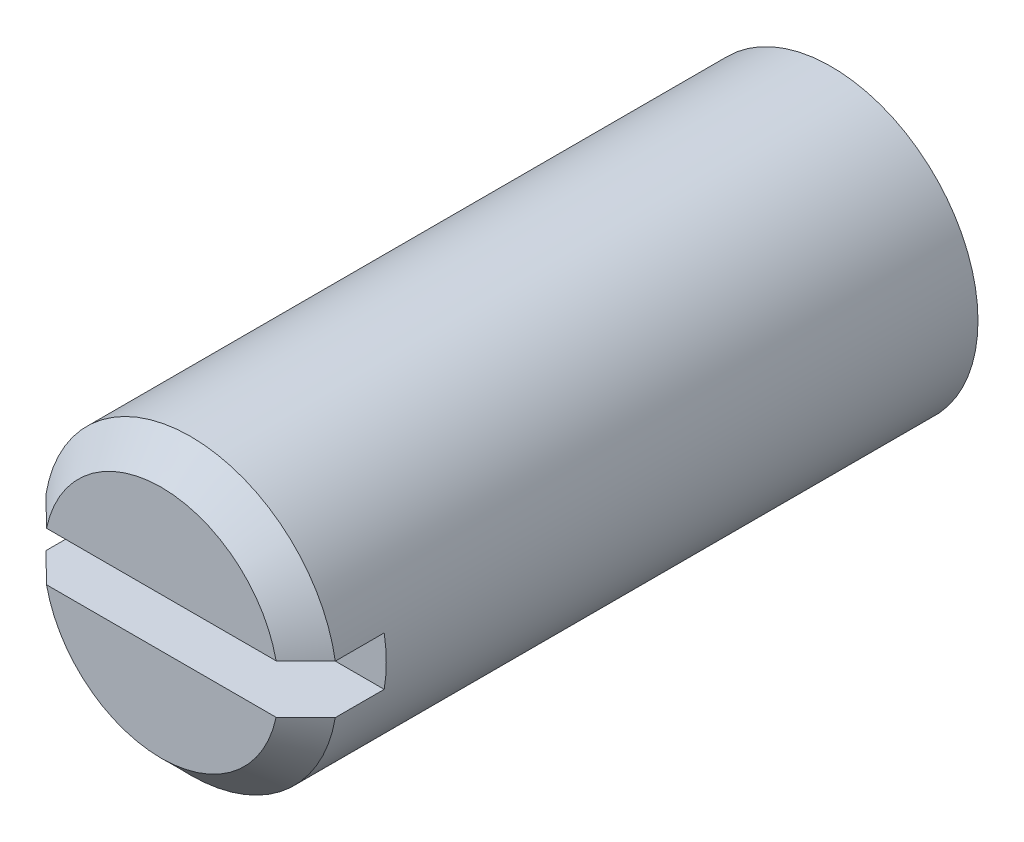
SolidWorks part; units mm, degrees
ref_plane "Спереди" through (0, 0, 0) normal (0, 0, 1) x (1, 0, 0)
ref_plane "Сверху" through (0, 0, 0) normal (0, 1, 0) x (1, 0, 0)
ref_plane "Справа" through (0, 0, 0) normal (1, 0, 0) x (0, 0, -1)
sketch "Эскиз1" plane through (0, 0, 0) normal (0, 1, 0) x (1, 0, 0)
  line L0 (0, 0) -> (-3, 0)
  line L1 (-3, 0) -> (-3, 13.701)
  line L2 (-0.75, 15) -> (0, 15)
  line L3 (0, 15) -> (0, 0)
  line L4 (-0.75, 15) -> (-3, 13.701)
  dimension "D1" = 0.75
  dimension "D2" = 3
  dimension "D3" = 15
  dimension "D4" = 60
revolve "Повернуть1" add sketch "Эскиз1" angle 360 about L3
sketch "Эскиз2" plane through (0, 0, 0) normal (1, 0, 0) x (0, 0, -1)
  line L0 (0, 0) -> (50000, 0) construction
  line L1 (0, -0.5) -> (0, 0.5)
  line L2 (0, 3) -> (0, -3) construction
  line L3 (0, 0.5) -> (1.6, 0.5)
  line L4 (0, -0.5) -> (1.6, -0.5)
  line L5 (1.6, 0.5) -> (1.6, -0.5)
  point P8 (0, 0)
  point P10 (1.6, 0)
  dimension "D1" = 1
  dimension "D2" = 1.6
extrude "Вырез-Вытянуть1" cut sketch "Эскиз2" against normal through all both and the other way through all
chamfer "Фаска1" distance 0.6 angle 45 2 edges at (0, -3, 0) (0, 3, 0)
